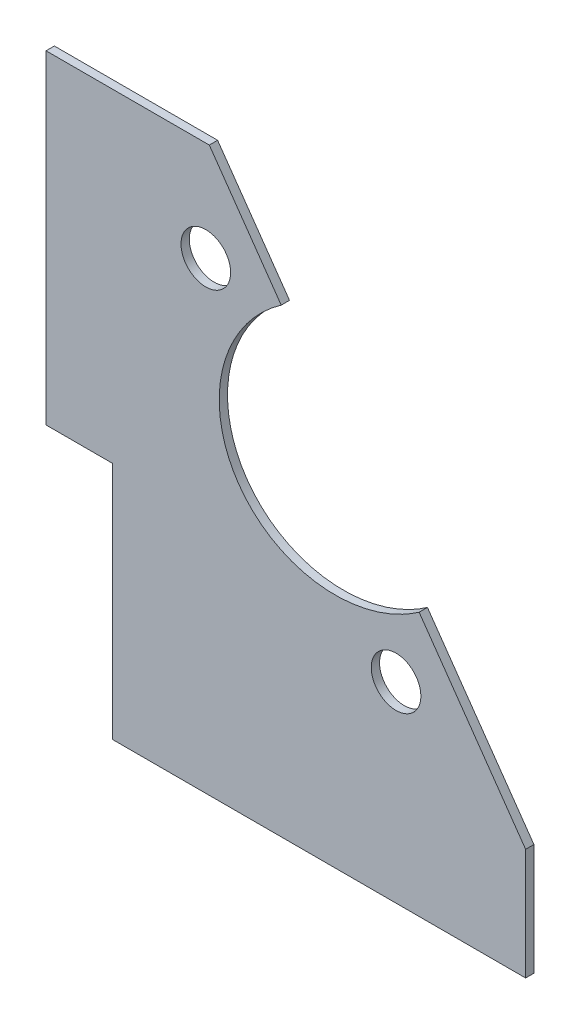
SolidWorks part; units mm, degrees
material "5052-H32"
ref_plane "Front Plane" through (0, 0, 0) normal (0, 0, 1) x (1, 0, 0)
ref_plane "Top Plane" through (0, 0, 0) normal (0, 1, 0) x (1, 0, 0)
ref_plane "Right Plane" through (0, 0, 0) normal (1, 0, 0) x (0, 0, -1)
sketch "Sketch1" plane through (0, 0, 0) normal (0, 0, 1) x (1, 0, 0)
  line L0 (0, 0) -> (85, 0)
  line L1 (85, 0) -> (58.623, 37.6703)
  line L2 (0, 121.3926) -> (0, 95) construction
  line L3 (0, 95) -> (12.4005, 103.6829)
  line L4 (0, 95) -> (0, 0)
  line L5 (12.4005, 103.6829) -> (0, 121.3926) construction
  line L6 (32.2384, 75.3513) -> (12.4005, 103.6829)
  line L7 (58.623, 37.6703) -> (32.2384, 75.3513) construction
  ellipse E0 centre (45.4307, 56.5108) end of major axis (66.7287, 71.4238) minor radius 23 (32.2384, 75.3513) -> (58.623, 37.6703) ccw
  ellipse E1 centre (45.4307, 56.5108) end of major axis (66.7287, 71.4238) minor radius 23 (58.623, 37.6703) -> (32.2384, 75.3513) ccw construction
  dimension "D1" = 85
  dimension "D2" = 55
  dimension "D3" = 95
  dimension "D4" = 46
  dimension "D5" = 52
  dimension "D6" = 37.6703
extrude "Boss-Extrude1" add sketch "Sketch1" along normal blind 1.5875 contours E0 L6 L3 L4 L0 L1
sketch "Sketch2" plane through (0, 0, 1.5875) normal (0, 0, 1) x (1, 0, 0)
  line L0 (17.8137, 75.9023) -> (54.2072, 23.9271) construction
  line L1 (32.2384, 75.3513) -> (12.4005, 103.6829) construction
  line L2 (32.2384, 75.3513) -> (58.623, 37.6703) construction
  line L3 (45.4307, 56.5108) -> (0, 24.6999) construction
  line L5 (0, 95) -> (0, 0) construction
  circle A0 centre (17.8137, 75.9023) radius 4.75
  circle A1 centre (54.2072, 23.9271) radius 4.75
  point P16 (36.0105, 49.9147)
  dimension "D1" = 9.5
  dimension "D2" = 63.45
  dimension "D3" = 11.5
extrude "Cut-Extrude1" cut sketch "Sketch2" against normal through all
sketch "Sketch3" plane through (0, 0, 1.5875) normal (0, 0, 1) x (1, 0, 0)
  line L0 (79, 8.5689) -> (79, 0)
  line L1 (85, 0) -> (58.623, 37.6703) construction
  line L2 (0, 0) -> (85, 0) construction
  line L3 (79, 0) -> (85, 0)
  line L4 (85, 0) -> (79, 8.5689)
  line L5 (0, 95) -> (18.4803, 95)
  line L6 (32.2384, 75.3513) -> (12.4005, 103.6829) construction
  line L7 (18.4803, 95) -> (12.4005, 103.6829)
  line L8 (12.4005, 103.6829) -> (0, 95)
  dimension "D1" = 6
extrude "Cut-Extrude2" cut sketch "Sketch3" against normal through all
sketch "Sketch4" plane through (0, 0, 0) normal (-1, 0, 0) x (0, 0, 1)
  line L0 (1.5875, 95) -> (1.5875, 0) construction
  line L1 (0, 95) -> (1.5875, 95)
  line L2 (0, 95) -> (0, 33)
  line L3 (0, 33) -> (1.5875, 33)
  line L4 (1.5875, 95) -> (1.5875, 33)
  line L5 (1.5875, 0) -> (0, 0) construction
  dimension "D1" = 33
extrude "Boss-Extrude2" add sketch "Sketch4" along normal blind 12.75
sketch "Sketch5" plane through (0, 0, 0) normal (0, -1, 0) x (1, 0, 0)
  line L0 (0, 0) -> (79, 0) construction
  line L1 (79, 1.5875) -> (0, 1.5875)
  line L2 (79, 1.5875) -> (79, 0)
  line L3 (79, 0) -> (0, 0)
  line L4 (0, 1.5875) -> (0, 0)
  line L8 (0, 0) -> (0, 1.5875) construction
extrude "Boss-Extrude3" add sketch "Sketch5" along normal blind 12.75
equation "\"D2@Sketch2\"=47.5+15.95"
equation "\"D3@Sketch2\"=9/2+7.0mm"
equation "\"D6@Sketch1\"=28.67032155+9"
